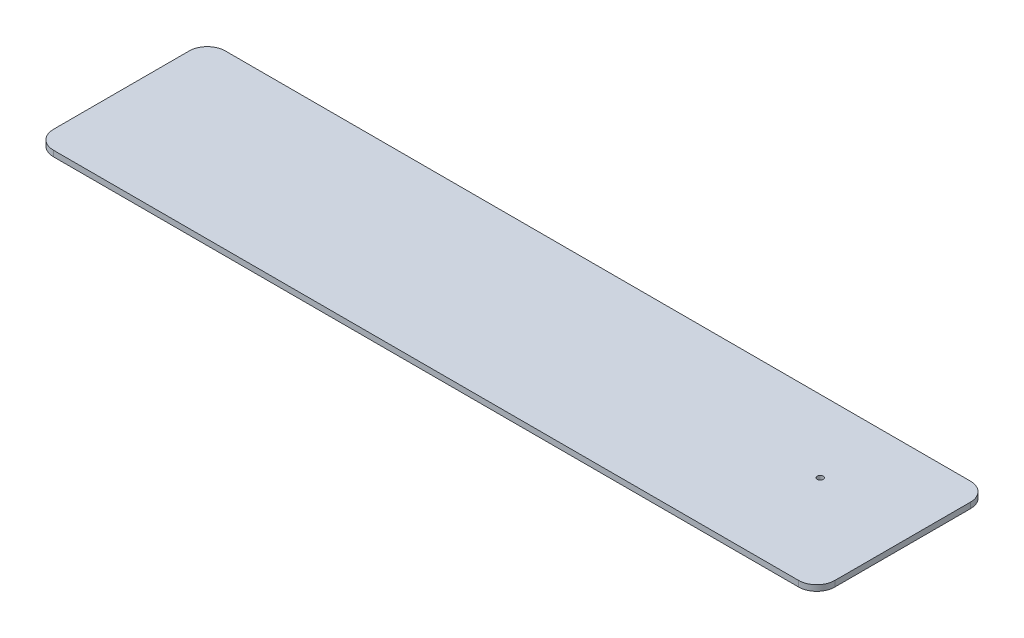
SolidWorks part; units mm, degrees
ref_plane "Front" through (0, 0, 0) normal (0, 0, 1) x (1, 0, 0)
ref_plane "Top" through (0, 0, 0) normal (0, 1, 0) x (1, 0, 0)
ref_plane "Right" through (0, 0, 0) normal (1, 0, 0) x (0, 0, -1)
sketch "Sketch1" plane through (0, 0, 0) normal (0, 1, 0) x (1, 0, 0)
  line L1 (-2.1325, 0) -> (429.6675, 0)
  line L2 (-2.1325, 0) -> (-2.1325, 95)
  line L3 (-2.1325, 95) -> (429.6675, 95)
  line L4 (429.6675, 0) -> (429.6675, 95)
  circle A0 centre (376.4915, 55.1167) radius 1.65
  dimension "D1" = 95
  dimension "D2" = 431.8
extrude "Boss-Extrude1" add sketch "Sketch1" along normal blind 3.175
fillet "Fillet1" radius 10 4 edges at (429.6675, 1.5875, -95) (429.6675, 1.5875, 0) (-2.1325, 1.5875, 0) (-2.1325, 1.5875, -95)
